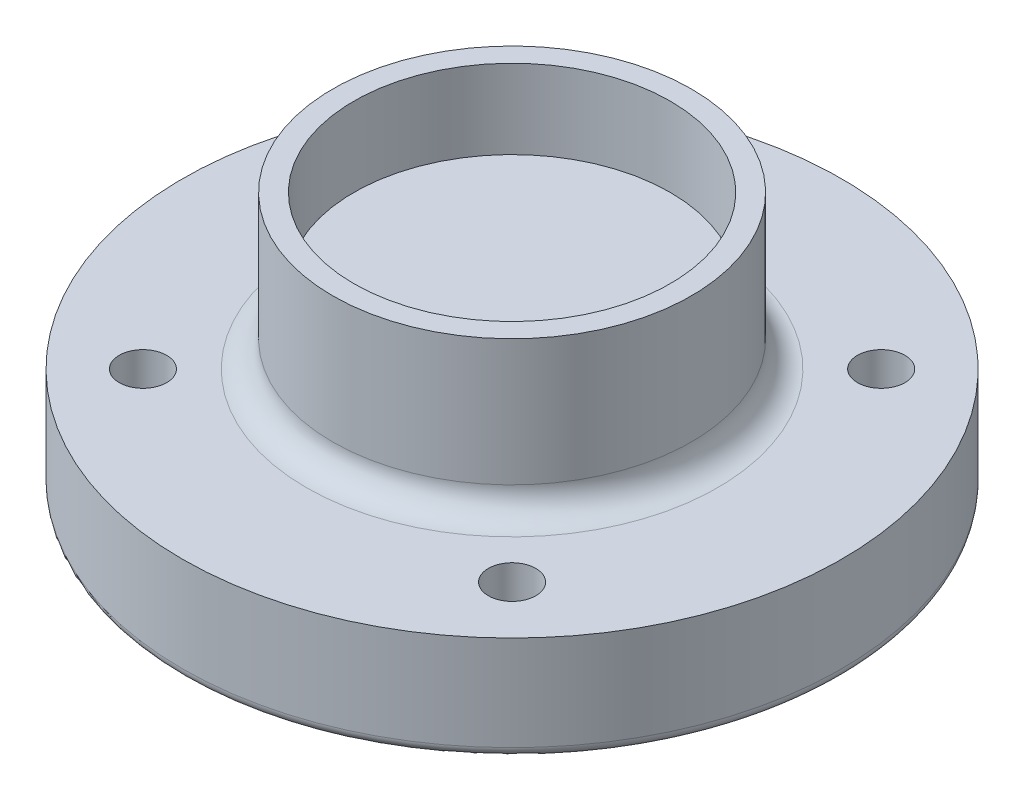
SolidWorks part; units mm, degrees
ref_plane "Front Plane" through (0, 0, 0) normal (0, 0, 1) x (1, 0, 0)
ref_plane "Top Plane" through (0, 0, 0) normal (0, 1, 0) x (1, 0, 0)
ref_plane "Right Plane" through (0, 0, 0) normal (1, 0, 0) x (0, 0, -1)
sketch "Sketch1" plane through (0, 0, 0) normal (0, 1, 0) x (1, 0, 0)
  circle A0 centre (0, 0) radius 62.5
  dimension "D1" = 125
extrude "Boss-Extrude1" add sketch "Sketch1" along normal blind 20
sketch "Sketch2" plane through (0, 20, 0) normal (0, 1, 0) x (1, 0, 0)
  circle A0 centre (0, 0) radius 34
  dimension "D1" = 68
extrude "Boss-Extrude2" add sketch "Sketch2" along normal blind 29
sketch "Sketch6" plane through (0, 49, 0) normal (0, 1, 0) x (1, 0, 0)
  circle A2 centre (0, 0) radius 30
  circle A3 centre (0, 0) radius 30
  dimension "D1" = 4
extrude "Cut-Extrude1" cut sketch "Sketch6" against normal blind 15
fillet "Fillet1" radius 5 1 edges at (0, 20, 34)
sketch "Sketch7" plane through (0, 0, 0) normal (0, -1, 0) x (1, 0, 0)
  line L1 (-35, 35) -> (35, 35) construction
  line L2 (-35, 35) -> (-35, -35) construction
  line L3 (-35, -35) -> (35, -35) construction
  line L4 (35, 35) -> (35, -35) construction
  line L5 (-35, 35) -> (35, -35) construction
  line L6 (-35, -35) -> (35, 35) construction
  point P0 (0, 0)
  dimension "D1" = 70
  dimension "D2" = 70
hole_wizard "CBORE for M8 Hex Head Bolt1" positions "3DSketch1" profile "Sketch12" counterbore size "M8" standard "ISO" end condition through all
sketch3d "3DSketch1"
  point P0 (-35, 0, 35)
  point P3 (35, 0, 35)
  point P6 (35, 0, -35)
  point P9 (-35, 0, -35)
sketch "Sketch12" plane through (-35, 0, 35) normal (1, 0, 0) x (0, 0, -1)
  line L0 (0, 0) -> (0, 49)
  line L1 (0, 49) -> (4.5, 49)
  line L3 (4.5, 49) -> (4.5, 5.3)
  line L4 (4.5, 5.3) -> (9.0055, 5.3)
  line L5 (9.0055, 5.3) -> (9.0055, 0)
  line L7 (9.0055, 0) -> (0, 0)
  line L11 (0, -6.35) -> (0, 107.95) construction
  dimension "Thru Hole Dia." = 9
  dimension "Thru Hole Depth" = 49
  dimension "C'Bore Dia." = 18.011
  dimension "C'Bore Depth" = 5.3
fillet "Fillet2" radius 2 1 edges at (0, 0, 62.5)
